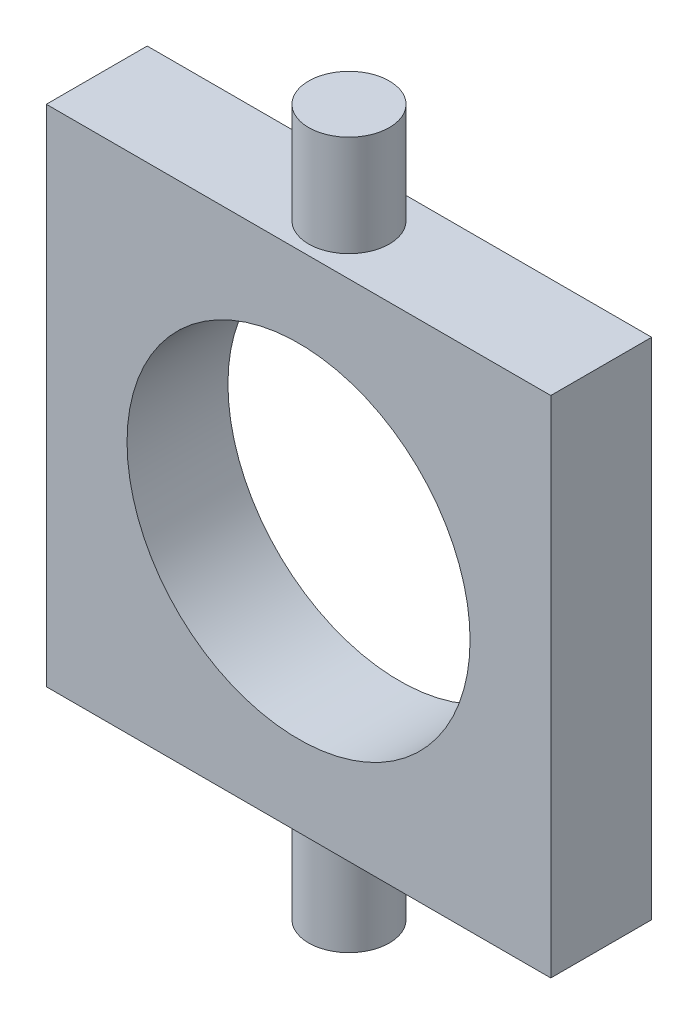
SolidWorks part; units mm, degrees
ref_plane "Front Plane" through (0, 0, 0) normal (0, 0, 1) x (1, 0, 0)
ref_plane "Top Plane" through (0, 0, 0) normal (0, 1, 0) x (1, 0, 0)
ref_plane "Right Plane" through (0, 0, 0) normal (1, 0, 0) x (0, 0, -1)
sketch "Sketch1" plane through (0, 0, 0) normal (0, 0, 1) x (1, 0, 0)
  line L1 (-25, 25) -> (25, 25)
  line L2 (-25, 25) -> (-25, -25)
  line L3 (-25, -25) -> (25, -25)
  line L4 (25, 25) -> (25, -25)
  line L5 (-25, 25) -> (25, -25) construction
  line L6 (-25, -25) -> (25, 25) construction
  point P0 (0, 0)
  dimension "D1" = 50
  dimension "D2" = 50
extrude "Boss-Extrude1" add sketch "Sketch1" along normal blind 10
sketch "Sketch2" plane through (0, 0, 10) normal (0, 0, 1) x (1, 0, 0)
  circle A0 centre (0, 0) radius 17
  dimension "D1" = 34
extrude "Cut-Extrude1" cut sketch "Sketch2" against normal blind 10
sketch "Sketch3" plane through (0, 25, 0) normal (0, 1, 0) x (1, 0, 0)
  circle A0 centre (0, -5) radius 4
  dimension "D1" = 8
extrude "Boss-Extrude2" add sketch "Sketch3" along normal blind 10
mirror "Mirror1" about plane through (0, 0, 0) normal (0, 1, 0) of "Boss-Extrude2"
